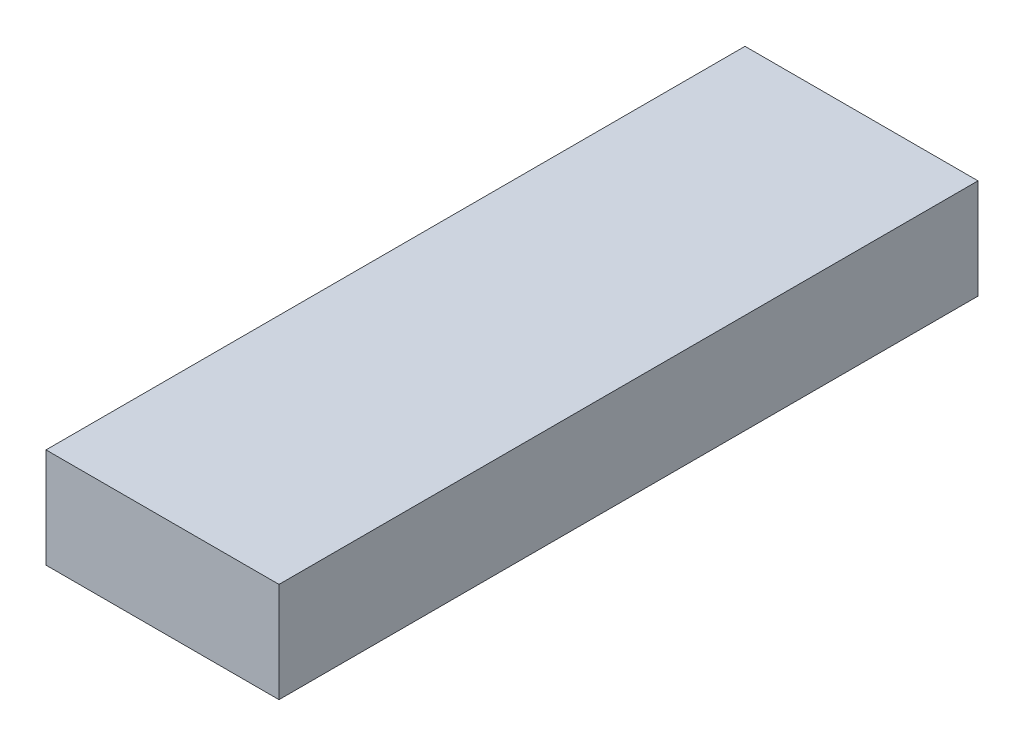
SolidWorks part; units mm, degrees
ref_plane "Alzado" through (0, 0, 0) normal (0, 0, 1) x (1, 0, 0)
ref_plane "Planta" through (0, 0, 0) normal (0, 1, 0) x (1, 0, 0)
ref_plane "Vista lateral" through (0, 0, 0) normal (1, 0, 0) x (0, 0, -1)
sketch "Croquis1" plane through (0, 0, 0) normal (0, 0, 1) x (1, 0, 0)
  line L0 (0, 0) -> (7, 0)
  line L1 (0, 0) -> (0, 3)
  line L2 (0, 3) -> (7, 3)
  line L3 (7, 3) -> (7, 0)
  dimension "D1" = 7
  dimension "D2" = 3
extrude "Saliente-Extruir1" add sketch "Croquis1" along normal blind 21
